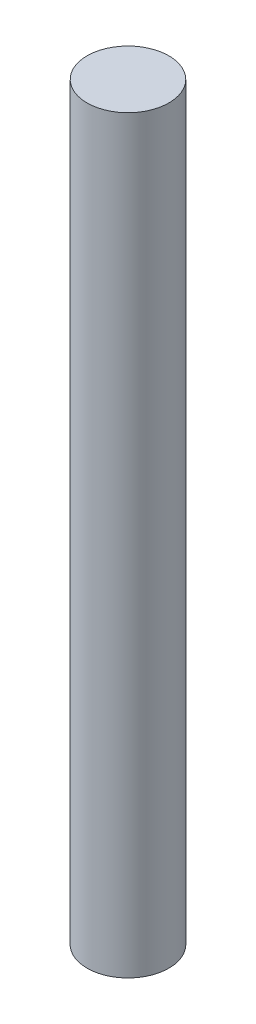
SolidWorks part; units mm, degrees
ref_plane "Front Plane" through (0, 0, 0) normal (0, 0, 1) x (1, 0, 0)
ref_plane "Top Plane" through (0, 0, 0) normal (0, 1, 0) x (1, 0, 0)
ref_plane "Right Plane" through (0, 0, 0) normal (1, 0, 0) x (0, 0, -1)
sketch "Sketch1" plane through (0, 0, 0) normal (0, 1, 0) x (1, 0, 0)
  circle A0 centre (0, 0) radius 1.5
  dimension "D1" = 3
extrude "Boss-Extrude1" add sketch "Sketch1" along normal mid plane 27.5
